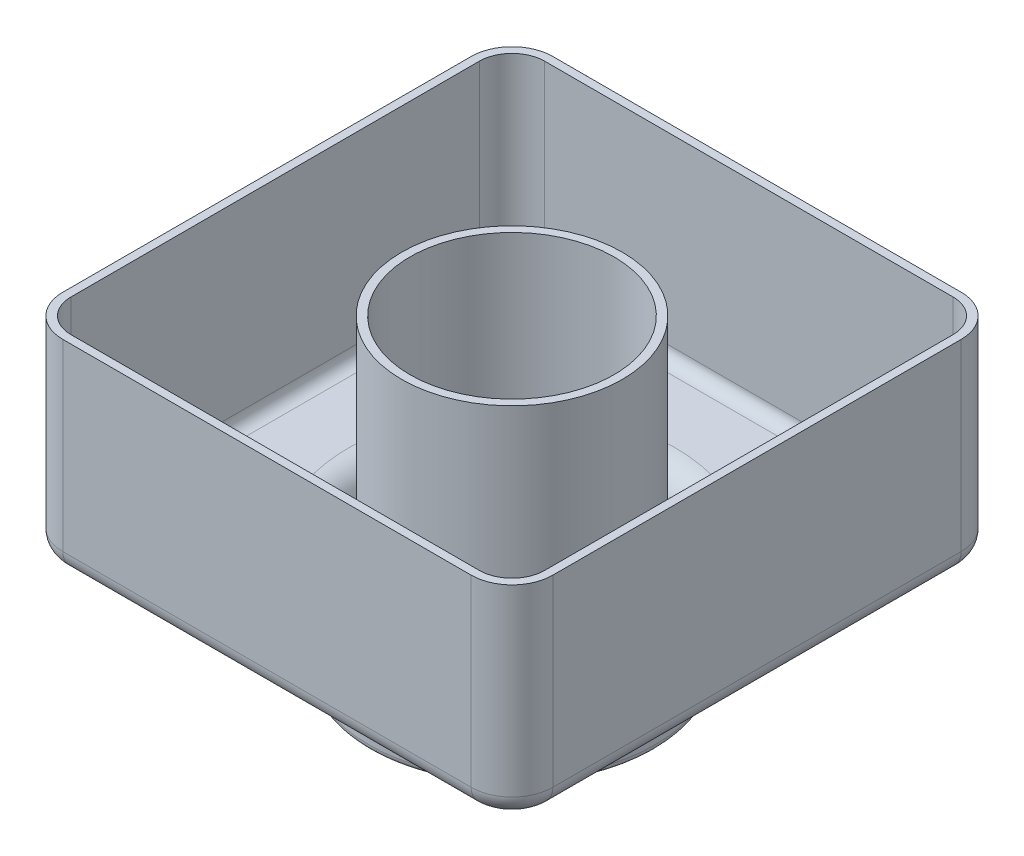
SolidWorks part; units mm, degrees
ref_plane "前视基准面" through (0, 0, 0) normal (0, 0, 1) x (1, 0, 0)
ref_plane "上视基准面" through (0, 0, 0) normal (0, 1, 0) x (1, 0, 0)
ref_plane "右视基准面" through (0, 0, 0) normal (1, 0, 0) x (0, 0, -1)
other "Configuration Table"
sketch "草图1" plane through (0, 0, 0) normal (0, 1, 0) x (1, 0, 0)
  line L1 (0, 0) -> (120, 0)
  line L2 (0, 0) -> (0, 120)
  line L3 (0, 120) -> (120, 120)
  line L4 (120, 0) -> (120, 120)
  dimension "D1" = 120
  dimension "D2" = 120
extrude "凸台-拉伸1" add sketch "草图1" along normal blind 50
sketch "草图3" plane through (0, 0, 0) normal (0, -1, 0) x (1, 0, 0)
  line L0 (0, 0) -> (120, 0) construction
  line L1 (120, 0) -> (120, -120) construction
  circle A0 centre (60, -60) radius 35
  dimension "D1" = 70
  dimension "D2" = 60
  dimension "D3" = 60
extrude "凸台-拉伸2" add sketch "草图3" along normal blind 25
sketch "草图4" plane through (0, -25, 0) normal (0, -1, 0) x (1, 0, 0)
  circle A0 centre (60, -60) radius 25
  dimension "D1" = 50
extrude "切除-拉伸1" cut sketch "草图4" against normal through all
fillet "圆角1" radius 10 4 edges at (120, 25, -120) (0, 25, -120) (0, 25, 0) (120, 25, 0)
fillet "圆角2" radius 1.5 2 edges at (60, -25, -95) (60, -25, -85)
fillet "圆角3" radius 5 9 edges at (2.9289, 0, -117.0711) (0, 0, -60) (2.9289, 0, -2.9289) (60, 0, 0) (117.0711, 0, -2.9289) (120, 0, -60) (117.0711, 0, -117.0711) (60, 0, -120) (60, 0, -95)
shell "抽壳1" thickness 2
